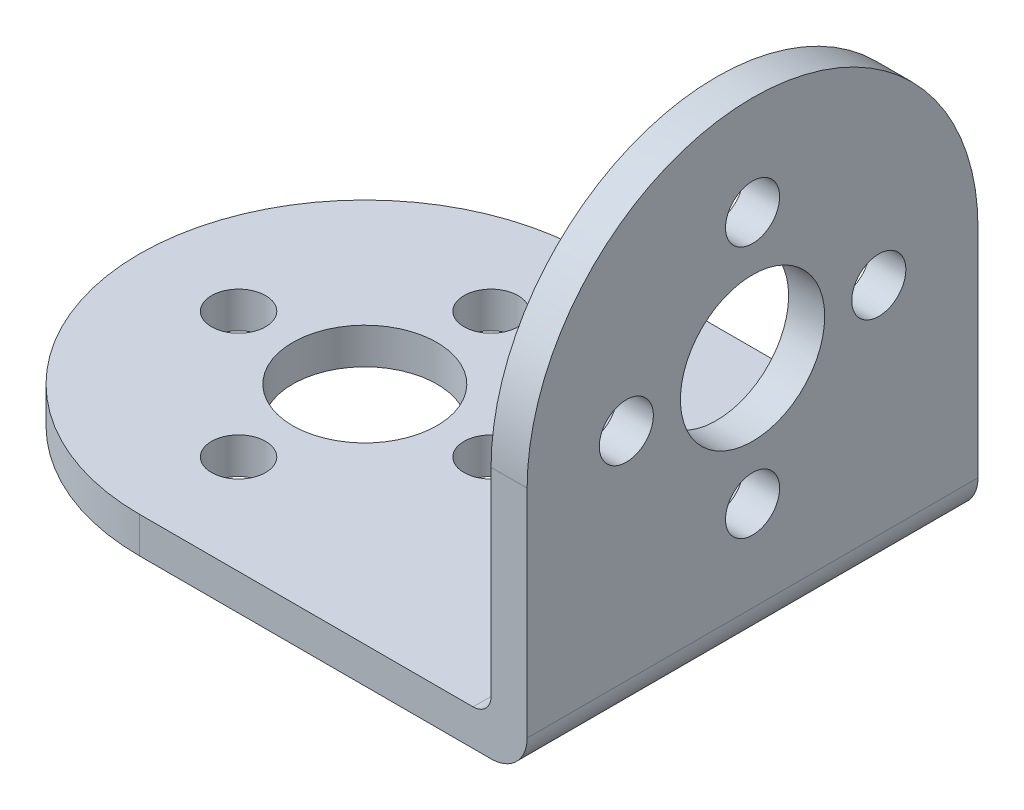
SolidWorks part; units mm, degrees
ref_plane "Front Plane" through (0, 0, 0) normal (0, 0, 1) x (1, 0, 0)
ref_plane "Top Plane" through (0, 0, 0) normal (0, 1, 0) x (1, 0, 0)
ref_plane "Right Plane" through (0, 0, 0) normal (1, 0, 0) x (0, 0, -1)
sketch "Sketch1" plane through (0, 0, 0) normal (0, 1, 0) x (1, 0, 0)
  line L0 (0, 12.5) -> (0, -12.5)
  line L1 (-19.5, 12.5) -> (0, 12.5)
  line L3 (-19.5, -12.5) -> (0, -12.5)
  arc A0 (-19.5, 12.5) -> (-19.5, -12.5) centre (-19.5, 0) ccw
  circle A2 centre (-19.5, 0) radius 7 construction
  circle A4 centre (-19.5, 0) radius 4
  circle A6 centre (-19.5, 7) radius 1.5
  circle A7 centre (-19.5, -7) radius 1.5
  circle A8 centre (-12.5, 0) radius 1.5
  circle A9 centre (-26.5, 0) radius 1.5
  dimension "D4" = 14
  dimension "D3" = 12.5
  dimension "D7" = 8
  dimension "D9" = 3
  dimension "D10" = 3
  dimension "D11" = 3
  dimension "D12" = 3
  dimension "D1" = 19.5
extrude "Boss-Extrude1" add sketch "Sketch1" along normal blind 2
sketch "Sketch2" plane through (0, 0, 0) normal (1, 0, 0) x (0, 0, -1)
  line L1 (-12.5, 0) -> (12.5, 0)
  line L2 (-12.5, 0) -> (-12.5, 14)
  line L4 (12.5, 0) -> (12.5, 14)
  arc A0 (-12.5, 14) -> (12.5, 14) centre (0, 14) cw
  circle A1 centre (0, 14) radius 7 construction
  circle A2 centre (0, 14) radius 4
  circle A3 centre (0, 21) radius 1.5
  circle A4 centre (7, 14) radius 1.5
  circle A5 centre (0, 7) radius 1.5
  circle A6 centre (-7, 14) radius 1.5
  dimension "D2" = 3
  dimension "D3" = 3
  dimension "D4" = 3
  dimension "D5" = 14
  dimension "D6" = 3
  dimension "D7" = 8
  dimension "D1" = 14
extrude "Boss-Extrude2" add sketch "Sketch2" along normal blind 2
fillet "Fillet1" radius 1 1 edges at (0, 2, 0)
fillet "Fillet3" radius 2 1 edges at (2, 0, 0)
